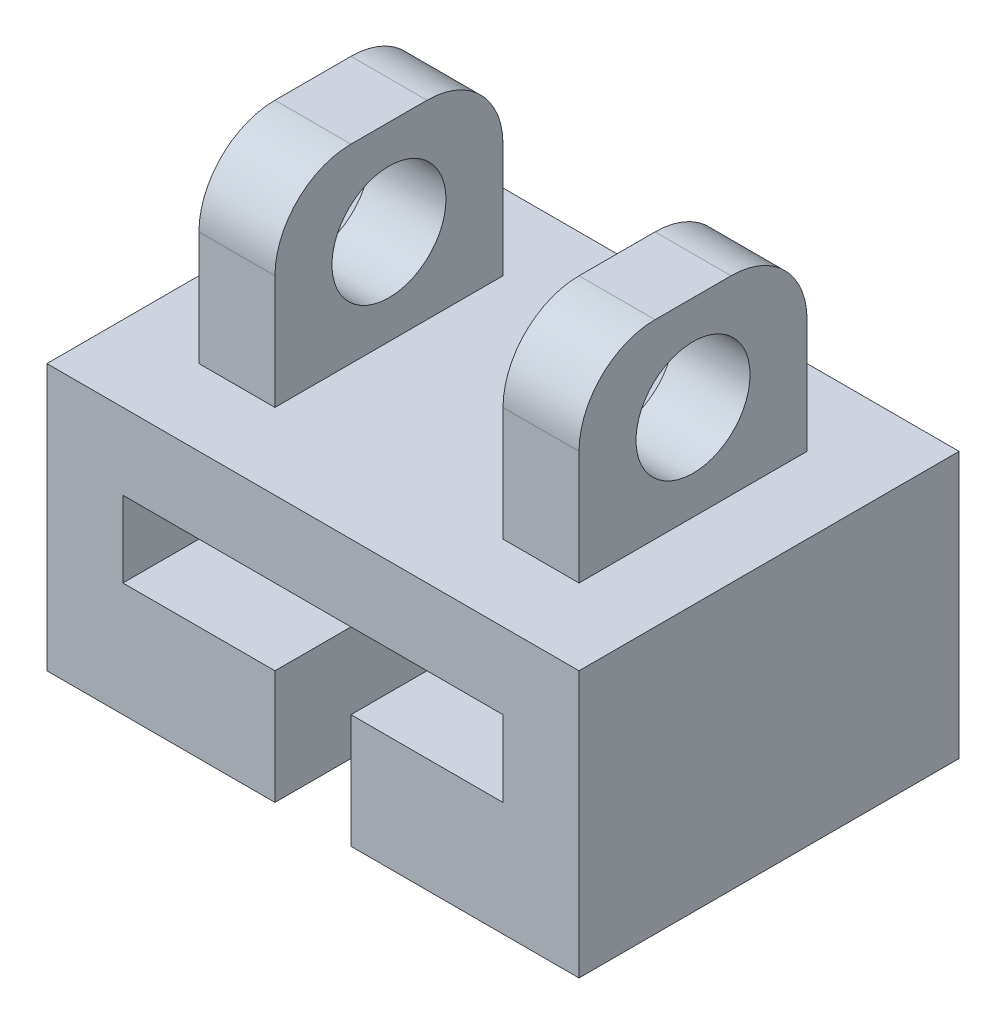
SolidWorks part; units mm, degrees
ref_plane "Front Plane" through (0, 0, 0) normal (0, 0, 1) x (1, 0, 0)
ref_plane "Top Plane" through (0, 0, 0) normal (0, 1, 0) x (1, 0, 0)
ref_plane "Right Plane" through (0, 0, 0) normal (1, 0, 0) x (0, 0, -1)
sketch "Sketch2" plane through (0, 0, 0) normal (0, 0, 1) x (1, 0, 0)
  line L1 (-80.8662, 3.6937) -> (59.1338, 3.6937)
  line L3 (-60.8662, -16.3063) -> (39.1338, -16.3063)
  line L4 (59.1338, 3.6937) -> (59.1338, -13.6937)
  line L5 (-20.8662, -66.3063) -> (-20.8662, -36.3063)
  line L6 (-60.8662, -36.3063) -> (-20.8662, -36.3063)
  line L8 (59.1338, -13.6937) -> (59.1338, -66.3063)
  line L9 (59.1338, -66.3063) -> (38.2676, -66.3063)
  line L10 (39.1338, -16.3063) -> (39.1338, -36.3063)
  line L11 (38.2676, -66.3063) -> (-0.8662, -66.3063)
  line L13 (39.1338, -36.3063) -> (-0.8662, -36.3063)
  line L14 (-0.8662, -66.3063) -> (-0.8662, -36.3063)
  line L15 (-60, -66.3063) -> (-20.8662, -66.3063)
  line L16 (-60.8662, -16.3063) -> (-60.8662, -36.3063)
  line L17 (-80.8662, -66.3063) -> (-60, -66.3063)
  line L18 (-80.8662, -13.6937) -> (-80.8662, -66.3063)
  line L19 (-80.8662, 3.6937) -> (-80.8662, -13.6937)
  point P0 (0, 0)
  point P20 (-21.7324, 0)
  dimension "D2" = 30
  dimension "D3" = 20
  dimension "D4" = 40
  dimension "D6" = 60
extrude "Boss-Extrude1" add sketch "Sketch2" along normal blind 100
sketch "Sketch3" plane through (0, 3.6937, 0) normal (0, 1, 0) x (1, 0, 0)
  line L0 (-80.8662, -100) -> (-80.8662, 0) construction
  line L1 (-60.8662, -20) -> (-40.8662, -20)
  line L2 (-60.8662, -20) -> (-60.8662, -80)
  line L3 (-60.8662, -80) -> (-40.8662, -80)
  line L4 (-40.8662, -20) -> (-40.8662, -80)
  line L5 (-60.8662, -20) -> (-40.8662, -80) construction
  line L6 (-60.8662, -80) -> (-40.8662, -20) construction
  line L7 (19.1338, -20) -> (39.1338, -20)
  line L8 (19.1338, -20) -> (19.1338, -80)
  line L9 (19.1338, -80) -> (39.1338, -80)
  line L10 (39.1338, -20) -> (39.1338, -80)
  line L11 (19.1338, -20) -> (39.1338, -80) construction
  line L12 (19.1338, -80) -> (39.1338, -20) construction
  line L13 (59.1338, -100) -> (59.1338, 0) construction
  line L14 (59.1338, 0) -> (-80.8662, 0) construction
  point P0 (-50.8662, -50)
  point P5 (29.1338, -50)
  dimension "D1" = 30
  dimension "D2" = 30
  dimension "D3" = 60
  dimension "D4" = 60
  dimension "D5" = 20
  dimension "D6" = 20
  dimension "D7" = 50
  dimension "D8" = 50
extrude "Boss-Extrude2" add sketch "Sketch3" along normal blind 50
fillet "Fillet1" radius 20 4 edges at (-50.8662, 53.6937, 80) (-50.8662, 53.6937, 20) (29.1338, 53.6937, 20) (29.1338, 53.6937, 80)
sketch "Sketch4" plane through (39.1338, 0, 0) normal (1, 0, 0) x (0, 0, -1)
  line L0 (-20, 33.6937) -> (-20, 3.6937) construction
  line L1 (-80, 3.6937) -> (-20, 3.6937) construction
  circle A0 centre (-50, 28.6937) radius 15
  dimension "D3" = 30
  dimension "D1" = 30
  dimension "D2" = 25
extrude "Cut-Extrude1" cut sketch "Sketch4" against normal blind 100
